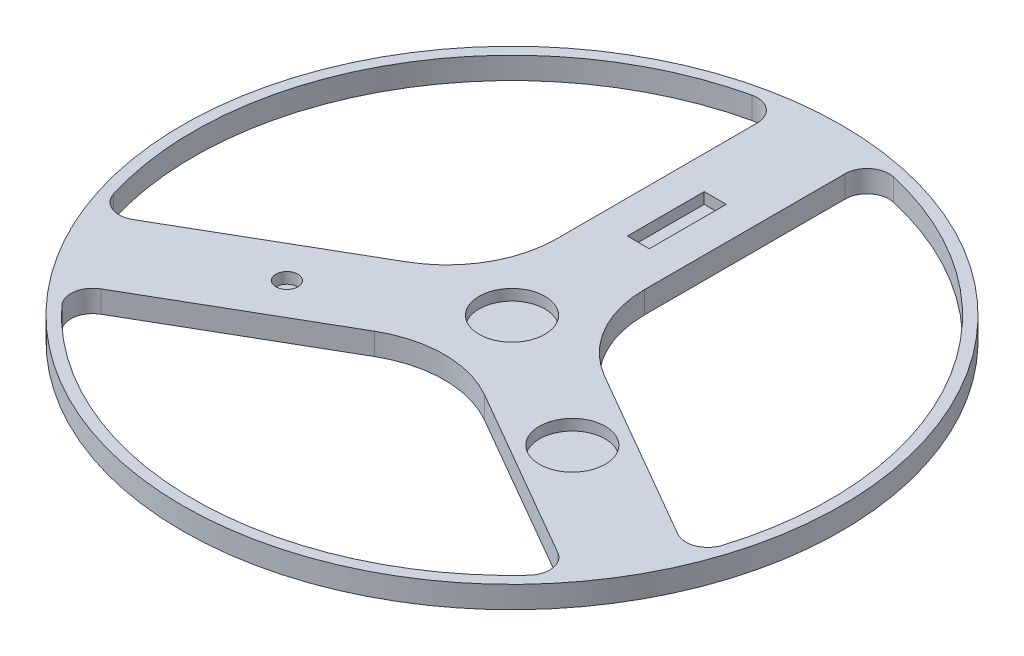
SolidWorks part; units mm, degrees
ref_plane "Front Plane" through (0, 0, 0) normal (0, 0, 1) x (1, 0, 0)
ref_plane "Top Plane" through (0, 0, 0) normal (0, 1, 0) x (1, 0, 0)
ref_plane "Right Plane" through (0, 0, 0) normal (1, 0, 0) x (0, 0, -1)
sketch "Sketch1" plane through (0, 0, 0) normal (0, 1, 0) x (1, 0, 0)
  line L0 (0, 0) -> (0, 29) construction
  line L1 (4, 28.7228) -> (4, 0)
  line L2 (-4, 0) -> (4, 0)
  line L3 (-4, 28.7228) -> (-4, 0)
  line L4 (22.8747, -17.8255) -> (-2, -3.4641)
  line L5 (26.8747, -10.8973) -> (2, 3.4641)
  line L6 (-26.8747, -10.8973) -> (-2, 3.4641)
  line L7 (-22.8747, -17.8255) -> (2, -3.4641)
  circle A0 centre (0, 0) radius 30
  circle A1 centre (0, 0) radius 29
  circle A2 centre (0, 0) radius 4
  point P10 (0, 0)
  point P11 (0, 0)
  point P21 (0, 0)
  dimension "D1" = 60
  dimension "D2" = 58
  dimension "D3" = 4
  dimension "D4" = 3
extrude "Boss-Extrude1" add sketch "Sketch1" along normal blind 2 contours A2 L3 L6 A1 L7 L4 | A2 L7 L4 A1 L5 L1 | A2 L1 L5 | A2 L4 L7 | A2 L6 L3 | A2 L2 | L2 L0 A2 | L0 L2 A2 | L0 A2 L5 L1 A1 | A2 L0 A1 L3 L6 | A0 A1 L3
fillet "Fillet1" radius 10 3 edges at (-4, 1, -2.3094) (0, 1, 4.6188) (4, 1, -2.3094)
fillet "Fillet2" radius 2 6 edges at (22.8747, 1, 17.8255) (26.8747, 1, 10.8973) (4, 1, -28.7228) (-4, 1, -28.7228) (-26.8747, 1, 10.8973) (-22.8747, 1, 17.8255)
sketch "Sketch2" plane through (0, 2, 0) normal (0, 1, 0) x (1, 0, 0)
  circle A0 centre (0, 0) radius 3
  dimension "D1" = 6
extrude "Cut-Extrude1" cut sketch "Sketch2" against normal blind 1
sketch "Sketch3" plane through (0, 2, 0) normal (0, 1, 0) x (1, 0, 0)
  line L0 (-0.0004, 0.0006) -> (25.9809, -14.9997) construction
  line L1 (24.798, -9.6983) -> (9, -0.5774) construction
  line L2 (0.0007, 0) -> (-25.9806, -15.0003) construction
  line L3 (-0.0004, 0.0006) -> (-0.0004, 30) construction
  line L5 (0.9996, 11.5006) -> (-1.0004, 11.5006)
  line L6 (0.9996, 11.5006) -> (0.9996, 18.5006)
  line L7 (0.9996, 18.5006) -> (-1.0004, 18.5006)
  line L8 (-1.0004, 11.5006) -> (-1.0004, 18.5006)
  line L9 (0.9996, 11.5006) -> (-1.0004, 18.5006) construction
  line L10 (0.9996, 18.5006) -> (-1.0004, 11.5006) construction
  circle A0 centre (-0.0004, 0.0006) radius 15 construction
  circle A1 centre (0, 0) radius 30 construction
  circle A2 centre (-12.9902, -7.5003) radius 1
  circle A3 centre (12.99, -7.4994) radius 3
  circle A4 centre (0.0007, 0) radius 45.4989 construction
  point P7 (12.99, -7.4994)
  point P8 (-0.0004, 15.0006)
  point P13 (0, 0)
  point P14 (-12.9902, -7.5003)
  point P19 (-0.0004, 15.0006)
  point P24 (0, 0)
  dimension "D1" = 30
  dimension "D3" = 2
  dimension "D4" = 6
  dimension "D2" = 3
  dimension "D5" = 7
  dimension "D6" = 2
extrude "Cut-Extrude2" cut sketch "Sketch3" against normal blind 1
sketch "Sketch4" plane through (0, 2, 0) normal (0, 1, 0) x (1, 0, 0)
  line L0 (0, 0) -> (0, 30) construction
  line L1 (0, 0) -> (25.9808, -15) construction
  line L2 (0, 0) -> (-25.9808, -15) construction
  line L5 (-20.798, -16.6265) -> (-5, -7.5056) construction
  line L6 (24.798, -9.6983) -> (9, -0.5774) construction
  circle A0 centre (0, 0) radius 30 construction
  circle A1 centre (21.6506, -12.5) radius 3
  circle A2 centre (-21.6506, -12.5) radius 3
  circle A3 centre (0, 25) radius 3
  point P18 (0, 0)
  dimension "D1" = 6
  dimension "D2" = 5
  dimension "D3" = 3
extrude "Cut-Extrude3" [suppressed] cut sketch "Sketch4" against normal blind 1
